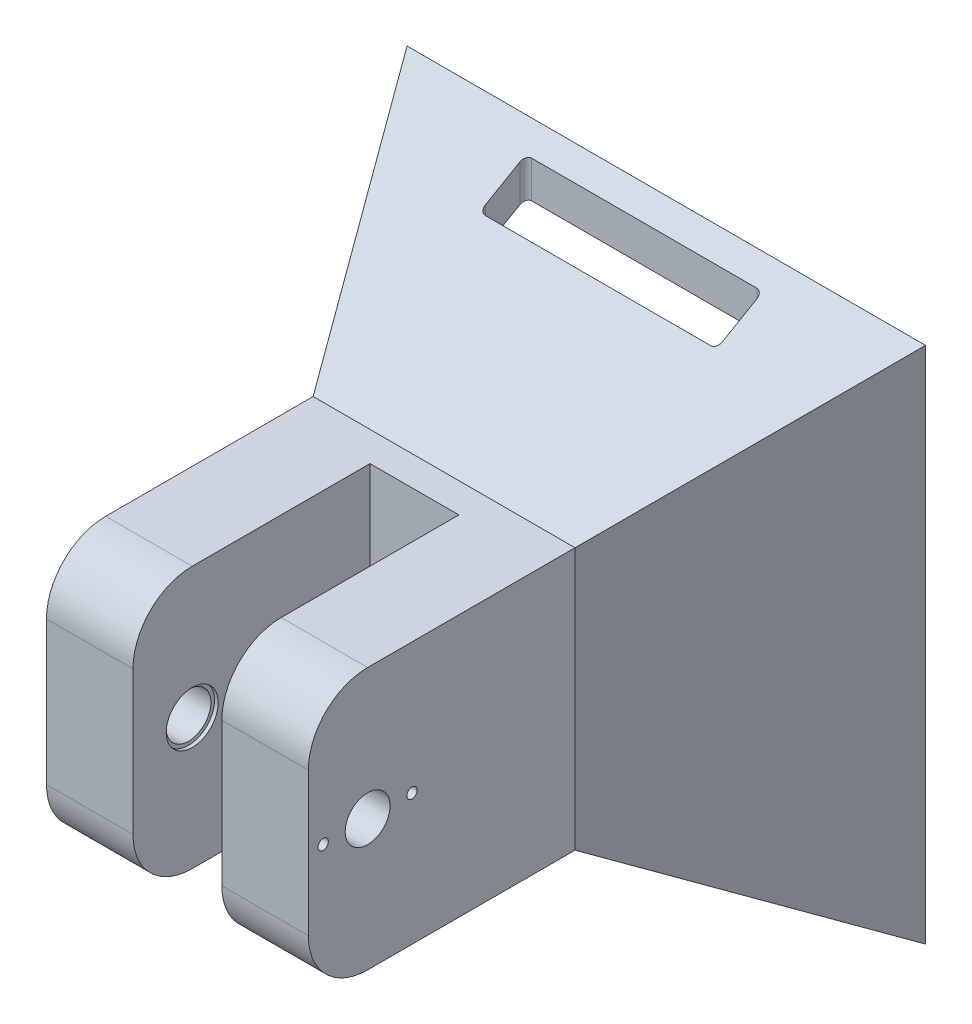
SolidWorks part; units mm, degrees
ref_plane "Front Plane" through (0, 0, 0) normal (0, 0, 1) x (1, 0, 0)
ref_plane "Top Plane" through (0, 0, 0) normal (0, 1, 0) x (1, 0, 0)
ref_plane "Right Plane" through (0, 0, 0) normal (1, 0, 0) x (0, 0, -1)
sketch "Sketch2" plane through (0, 0, 0) normal (0, 0, 1) x (1, 0, 0)
  line L1 (0, 0) -> (175, 0)
  line L2 (0, 0) -> (0, 175)
  line L3 (0, 175) -> (175, 175)
  line L4 (175, 0) -> (175, 175)
  dimension "D1" = 175
  dimension "D2" = 175
extrude "Boss-Extrude1" add sketch "Sketch2" along normal blind 75 draft 30
sketch "Sketch3" plane through (0, 0, 75) normal (0, 0, 1) x (1, 0, 0)
  line L4 (43.3013, 131.6987) -> (43.3013, 43.3013)
  line L5 (43.3013, 43.3013) -> (131.6987, 43.3013)
  line L6 (131.6987, 43.3013) -> (131.6987, 131.6987)
  line L7 (131.6987, 131.6987) -> (43.3013, 131.6987)
  line L8 (43.3013, 131.6987) -> (43.3013, 43.3013)
  line L9 (43.3013, 43.3013) -> (131.6987, 43.3013)
  line L10 (131.6987, 43.3013) -> (131.6987, 131.6987)
  line L11 (131.6987, 131.6987) -> (43.3013, 131.6987)
  dimension "D1" = 0
extrude "Boss-Extrude2" add sketch "Sketch3" along normal blind 90
sketch "Sketch4" plane through (0, 0, 165) normal (0, 0, 1) x (1, 0, 0)
  line L0 (131.6987, 131.6987) -> (43.3013, 131.6987) construction
  line L1 (72.5, 131.6987) -> (102.5, 131.6987)
  line L2 (72.5, 131.6987) -> (72.5, 43.3013)
  line L3 (72.5, 43.3013) -> (102.5, 43.3013)
  line L4 (102.5, 131.6987) -> (102.5, 43.3013)
  line L5 (43.3013, 43.3013) -> (131.6987, 43.3013) construction
  point P8 (87.5, 131.6987)
  point P9 (87.5, 131.6987)
  dimension "D1" = 30
extrude "Cut-Extrude1" cut sketch "Sketch4" against normal blind 80
fillet "Fillet1" radius 20 4 edges at (57.9006, 43.3013, 165) (117.0994, 43.3013, 165) (117.0994, 131.6987, 165) (57.9006, 131.6987, 165)
sketch "Sketch5" plane through (43.3013, 0, 0) normal (-1, 0, 0) x (0, 0, 1)
  line L0 (165, 111.6987) -> (165, 63.3013) construction
  circle A0 centre (145, 87.5) radius 7.575
  point P4 (165, 87.5)
  dimension "D2" = 15.15
  dimension "D1" = 20
extrude "Cut-Extrude2" cut sketch "Sketch5" against normal up to surface (88.3975 mm away) up to face at (131.6987, 87.5, 129.714)
sketch "Sketch6" plane through (0, 0, 0) normal (0, 0, -1) x (-1, 0, 0)
  line L0 (-175, 0) -> (-175, 175) construction
  line L1 (-12.5, 162.5) -> (-162.5, 162.5)
  line L2 (-12.5, 162.5) -> (-12.5, 12.5)
  line L3 (-12.5, 12.5) -> (-162.5, 12.5)
  line L4 (-162.5, 162.5) -> (-162.5, 12.5)
  line L5 (-175, 175) -> (0, 175) construction
  point P4 (-162.5, 87.5)
  point P7 (-175, 87.5)
  point P8 (-87.5, 162.5)
  point P11 (-87.5, 175)
  dimension "D1" = 150
extrude "Cut-Extrude3" cut sketch "Sketch6" against normal blind 60 draft 30
sketch "Sketch8" plane through (131.6987, 0, 0) normal (1, 0, 0) x (0, 0, -1)
  arc A0 (-127.9, 87.5) -> (-132.1, 87.5) centre (-130, 87.5) ccw construction
  circle A1 centre (-130, 87.5) radius 2.1 construction
  arc A2 (-157.9, 87.5) -> (-162.1, 87.5) centre (-160, 87.5) ccw construction
  circle A3 centre (-160, 87.5) radius 2.1 construction
  circle A4 centre (-160, 87.5) radius 1.75
  circle A5 centre (-130, 87.5) radius 1.75
  dimension "D1" = 3.5
extrude "Cut-Extrude5" cut sketch "Sketch8" against normal up to surface (29.1987 mm away) up to face at (102.5, 95.075, 145)
sketch "Sketch9" plane through (102.5, 0, 0) normal (-1, 0, 0) x (0, 0, 1)
  circle A4 centre (160, 87.5) radius 3.25
  circle A5 centre (130, 87.5) radius 3.25
  circle A7 centre (130, 87.5) radius 1.75 construction
  circle A8 centre (160, 87.5) radius 1.75 construction
  circle A9 centre (130, 87.5) radius 1.75
  circle A10 centre (160, 87.5) radius 1.75
  dimension "D1" = 6.5
extrude "Cut-Extrude6" cut sketch "Sketch9" against normal blind 3
sketch "Sketch10" plane through (72.5, 0, 0) normal (1, 0, 0) x (0, 0, -1)
  circle A2 centre (-145, 87.5) radius 8.775
  circle A3 centre (-145, 87.5) radius 8.775
  dimension "D1" = 1.2
extrude "Cut-Extrude7" cut sketch "Sketch10" against normal blind 1.25
ref_plane "Plane1" through (87.5, 0, 0) normal (1, 0, 0) x (0, 0, -1)
mirror "Mirror1" about plane through (87.5, 0, 0) normal (1, 0, 0) of "Cut-Extrude7"
ref_plane "Plane2" through (0, 0, 15) normal (0, 0, -1) x (-1, 0, 0)
sketch "Sketch11" plane through (0, 0, 15) normal (0, 0, -1) x (-1, 0, 0)
  line L8 (-175, 0) -> (-175, 175) construction
  line L9 (-43.25, 144.75) -> (-131.75, 144.75) construction
  line L10 (-43.25, 144.75) -> (-43.25, 30.25) construction
  line L11 (-43.25, 30.25) -> (-131.75, 30.25) construction
  line L12 (0, 0) -> (0, 175)
  line L13 (0, 175) -> (-175, 175)
  line L14 (-175, 175) -> (-175, 0)
  line L15 (-175, 0) -> (0, 0)
  line L16 (0, 0) -> (0, 175) construction
  line L17 (0, 175) -> (-175, 175) construction
  line L18 (-175, 175) -> (-175, 0) construction
  line L19 (-175, 0) -> (0, 0) construction
  line L20 (-131.75, 144.75) -> (-131.75, 30.25) construction
  circle A0 centre (-43.25, 144.75) radius 1.05
  circle A1 centre (-43.25, 30.25) radius 1.05
  circle A2 centre (-131.75, 144.75) radius 1.05
  circle A3 centre (-131.75, 30.25) radius 1.05
  circle A4 centre (-43.25, 144.75) radius 2.5
  circle A5 centre (-43.25, 30.25) radius 2.5
  circle A6 centre (-131.75, 30.25) radius 2.5
  circle A7 centre (-131.75, 144.75) radius 2.5
  point P10 (-175, 87.5)
  point P11 (-131.75, 87.5)
  point P12 (-87.5, 144.75)
  point P13 (-87.5, 175)
  dimension "D4" = 2.1
  dimension "D5" = 5
  dimension "D2" = 114.5
  dimension "D3" = 88.5
  dimension "D1" = 0
extrude "Boss-Extrude3" add sketch "Sketch11" against normal up to body separate body
sketch "Sketch12" plane through (0, 0, 0) normal (-0.866, 0, 0.5) x (0.5, 0, 0.866)
  line L0 (86.6025, 131.6987) -> (86.6025, 43.3013) construction
  line L1 (62.6025, 102.75) -> (48.1025, 102.75)
  line L2 (62.6025, 102.75) -> (62.6025, 72.25)
  line L3 (62.6025, 72.25) -> (48.1025, 72.25)
  line L4 (48.1025, 102.75) -> (48.1025, 72.25)
  point P6 (86.6025, 87.5)
  point P7 (62.6025, 87.5)
  dimension "D1" = 30.5
  dimension "D2" = 14.5
  dimension "D3" = 24
extrude "Cut-Extrude8" cut sketch "Sketch12" against normal up to surface (10.8253 mm away) separate body up to face at (29.8205, 87.5, 30)
sketch "Sketch13" plane through (9.375, 0, -5.4127) normal (0.866, 0, -0.5) x (-0.5, 0, -0.866)
  line L1 (-68.1025, 66.45) -> (-42.8525, 66.45)
  line L2 (-68.1025, 66.45) -> (-68.1025, 111.45)
  line L3 (-68.1025, 111.45) -> (-42.8525, 111.45)
  line L4 (-42.8525, 66.45) -> (-42.8525, 111.45)
  line L5 (-62.6025, 72.25) -> (-48.1025, 72.25) construction
  line L6 (-48.1025, 72.25) -> (-48.1025, 102.75) construction
  dimension "D1" = 25.25
  dimension "D2" = 45
  dimension "D3" = 5.25
  dimension "D4" = 5.8
extrude "Cut-Extrude9" cut sketch "Sketch13" against normal offset from surface (8.3253 mm away) 2.5 up to face at (27.6763, 87.5, 47.9367)
sketch "Sketch15" plane through (2.1651, 0, -1.25) normal (0.866, 0, -0.5) x (-0.5, 0, -0.866)
  line L0 (-48.1025, 72.25) -> (-62.6025, 72.25) construction
  line L1 (-65.3525, 69.95) -> (-45.8525, 69.95) construction
  line L2 (-65.3525, 69.95) -> (-65.3525, 107.55) construction
  line L3 (-65.3525, 107.55) -> (-45.8525, 107.55) construction
  line L4 (-45.8525, 69.95) -> (-45.8525, 107.55) construction
  line L5 (-62.6025, 102.75) -> (-48.1025, 102.75) construction
  line L6 (-48.1025, 102.75) -> (-48.1025, 72.25) construction
  line L8 (-62.6025, 72.25) -> (-62.6025, 102.75) construction
  circle A0 centre (-65.3525, 69.95) radius 1.05
  circle A1 centre (-45.8525, 69.95) radius 1.05
  circle A2 centre (-65.3525, 107.55) radius 1.05
  circle A3 centre (-45.8525, 107.55) radius 1.05
  circle A4 centre (-65.3525, 69.95) radius 2.5
  circle A5 centre (-65.3525, 107.55) radius 2.5
  circle A6 centre (-45.8525, 107.55) radius 2.5
  circle A7 centre (-45.8525, 69.95) radius 2.5
  dimension "D5" = 2.1
  dimension "D6" = 5
  dimension "D1" = 2.3
  dimension "D2" = 4.8
  dimension "D3" = 2.25
  dimension "D4" = 2.75
extrude "Boss-Extrude6" add sketch "Sketch15" along normal blind 5
sketch "Sketch16" plane through (0, 0, 0) normal (-0.866, 0, 0.5) x (0.5, 0, 0.866)
  line L1 (72.8525, 126.85) -> (37.8525, 126.85)
  line L2 (72.8525, 126.85) -> (72.8525, 112.75)
  line L3 (72.8525, 112.75) -> (37.8525, 112.75)
  line L4 (37.8525, 126.85) -> (37.8525, 112.75)
  line L6 (62.6025, 102.75) -> (48.1025, 102.75) construction
  line L7 (62.6025, 102.75) -> (48.1025, 102.75) construction
  point P6 (55.3525, 102.75)
  point P7 (55.3525, 112.75)
  dimension "D1" = 14.1
  dimension "D2" = 35
  dimension "D3" = 10
extrude "Cut-Extrude10" cut sketch "Sketch16" against normal up to surface (10.8253 mm away) up to face at (37.1138, 88.95, 42.6323)
sketch "Sketch19" plane through (0, 0, 0) normal (-0.866, 0, 0.5) x (0.5, 0, 0.866)
  line L0 (37.8525, 119.8) -> (0, 119.8)
  line L1 (37.8525, 126.85) -> (37.8525, 112.75) construction
  line L2 (0, 175) -> (0, 0) construction
  line L3 (72.8525, 119.8) -> (86.6025, 119.8)
  line L4 (72.8525, 112.75) -> (72.8525, 126.85) construction
  line L5 (86.6025, 131.6987) -> (86.6025, 43.3013) construction
sketch "Sketch18" plane through (0, 0, 0) normal (-0.866, 0, 0.5) x (0.5, 0, 0.866)
  text T0 "<r-90>V</r>\r\n" font "Calibri" height 6
  point P1 (0, 0)
  point P2 (0, 0)
  point P3 (0, 0)
  point P4 (28.3632, 122.8452)
  point P5 (0, 0)
  point P6 (28.364, 122.5551)
  point P7 (28.3517, 122.75)
  point P8 (28.3584, 122.6643)
  point P9 (0, 0)
  point P10 (28.3511, 122.7182)
  point P11 (28.3514, 122.6709)
  point P12 (28.1536, 123.5083)
  point P13 (28.6022, 122.1415)
  point P14 (28.5731, 122.5929)
  point P15 (28.5661, 122.7715)
  point P16 (28.5679, 122.7028)
  point P17 (28.5659, 122.644)
  point P18 (28.5656, 122.6798)
sketch "Sketch20" plane through (0, 0, 0) normal (-0.866, 0, 0.5) x (0.5, 0, 0.866)
  text T0 "<r-90>F</r>" font "Calibri" height 6
  point P1 (74.7846, 121.6284)
  point P2 (0, 0)
  point P3 (74.7565, 121.9823)
  point P4 (74.7594, 122.0716)
  point P5 (75.0644, 122.0846)
extrude "Cut-Extrude11" cut sketch "Sketch18" against normal blind 1
extrude "Cut-Extrude12" cut sketch "Sketch20" against normal blind 1
sketch "Sketch21" plane through (0, 0, 0) normal (-0.866, 0, 0.5) x (0.5, 0, 0.866)
  line L1 (42.8525, 62.25) -> (67.8525, 62.25) construction
  line L2 (48.1025, 72.25) -> (62.6025, 72.25) construction
  circle A0 centre (67.8525, 62.25) radius 2.55
  circle A1 centre (42.8525, 62.25) radius 2.55
  point P7 (55.3525, 72.25)
  point P8 (55.3525, 62.25)
  point P9 (66.3911, 61.5123)
  point P10 (66.485, 61.4422)
  dimension "D1" = 5.1
  dimension "D2" = 10
  dimension "D3" = 25
extrude "Cut-Extrude13" cut sketch "Sketch21" against normal up to surface (10.8253 mm away) up to face at (37.0513, 119.8, 42.524)
sketch "Sketch22" plane through (9.375, 0, -5.4127) normal (0.866, 0, -0.5) x (-0.5, 0, -0.866)
  circle A0 centre (-42.8525, 62.25) radius 3.5
  circle A1 centre (-67.8525, 62.25) radius 3.5
  point P6 (-67.8525, 62.25)
  dimension "D1" = 7
extrude "Cut-Extrude14" cut sketch "Sketch22" against normal offset from surface (5.8253 mm away) 5 up to face at (35.2013, 62.25, 60.9704)
sketch "Sketch24" plane through (0, 0, 0) normal (-0.866, 0, 0.5) x (0.5, 0, 0.866)
  text T0 "<r-90>P         C</r>\r\n" font "Calibri" height 6
extrude "Cut-Extrude15" cut sketch "Sketch24" against normal blind 1
sketch "Sketch25" plane through (0, 131.25, 75.7772) normal (0, 0.866, 0.5) x (1, 0, 0)
  line L0 (131.6987, 0.8975) -> (43.3013, 0.8975) construction
  line L1 (127.5, 60.8975) -> (47.5, 60.8975)
  line L2 (127.5, 60.8975) -> (127.5, 78.8975)
  line L3 (127.5, 78.8975) -> (47.5, 78.8975)
  line L4 (47.5, 60.8975) -> (47.5, 78.8975)
  point P6 (87.5, 0.8975)
  point P7 (87.5, 60.8975)
  dimension "D1" = 60
  dimension "D2" = 80
  dimension "D3" = 18
extrude "Cut-Extrude16" cut sketch "Sketch25" along direction (0, -1, 0) on the side against the normal up to surface (148.3975 mm away)
fillet "Fillet3" radius 2 8 edges at (127.5, 10.5513, 7.45) (127.5, 19.5513, 23.0385) (47.5, 19.5513, 23.0385) (47.5, 10.5513, 7.45) (47.5, 164.4487, 7.45) (47.5, 155.4487, 23.0385) (127.5, 155.4487, 23.0385) (127.5, 164.4487, 7.45)
